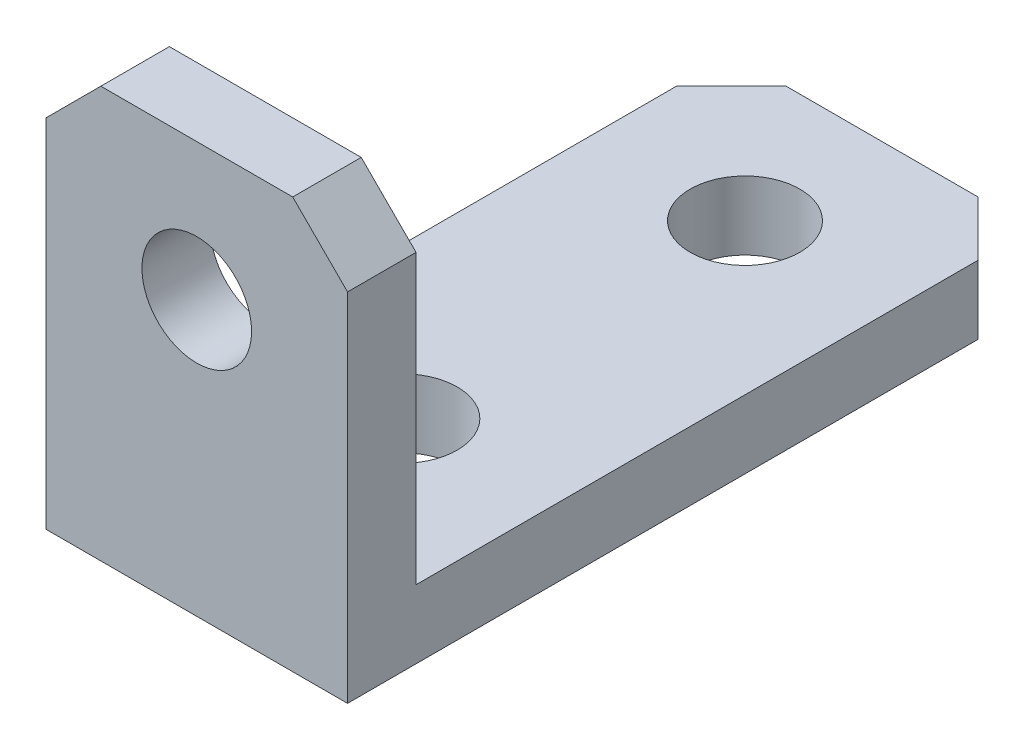
SolidWorks part; units mm, degrees
ref_plane "前视基准面" through (0, 0, 0) normal (0, 0, 1) x (1, 0, 0)
ref_plane "上视基准面" through (0, 0, 0) normal (0, 1, 0) x (1, 0, 0)
ref_plane "右视基准面" through (0, 0, 0) normal (1, 0, 0) x (0, 0, -1)
sketch "草图1" plane through (0, 0, 0) normal (0, 1, 0) x (1, 0, 0)
  line L0 (-2.0159, -28.8889) -> (-2.0159, -13.8889) construction
  line L1 (-13.0159, 21.1111) -> (8.9841, 21.1111)
  line L2 (-13.0159, 21.1111) -> (-13.0159, -28.8889)
  line L3 (-13.0159, -28.8889) -> (8.9841, -28.8889)
  line L4 (8.9841, 21.1111) -> (8.9841, -28.8889)
  line L5 (-2.0159, -13.8889) -> (-2.0159, 11.1111) construction
  circle A0 centre (-2.0159, 11.1111) radius 4
  circle A1 centre (-2.0159, -13.8889) radius 4
  dimension "D5" = 8
  dimension "D6" = 8
  dimension "D1" = 50
  dimension "D2" = 22
  dimension "D3" = 25
  dimension "D4" = 15
extrude "凸台-拉伸1" add sketch "草图1" along normal blind 5
sketch "草图2" plane through (0, 0, 28.8889) normal (0, 0, 1) x (1, 0, 0)
  line L0 (-2.0159, 5) -> (-2.0159, 20) construction
  line L1 (-13.0159, 5) -> (8.9841, 5) construction
  line L2 (-13.0159, 5) -> (8.9841, 5)
  line L3 (8.9841, 5) -> (8.9841, 30)
  line L4 (8.9841, 30) -> (-13.0159, 30)
  line L5 (-13.0159, 30) -> (-13.0159, 5)
  circle A0 centre (-2.0159, 20) radius 4
  dimension "D1" = 8
  dimension "D2" = 15
  dimension "D3" = 25
extrude "凸台-拉伸2" add sketch "草图2" against normal blind 5
chamfer "倒角1" distance 4 angle 45 4 edges at (-13.0159, 2.5, -21.1111) (8.9841, 2.5, -21.1111) (-13.0159, 30, 26.3889) (8.9841, 30, 26.3889)
